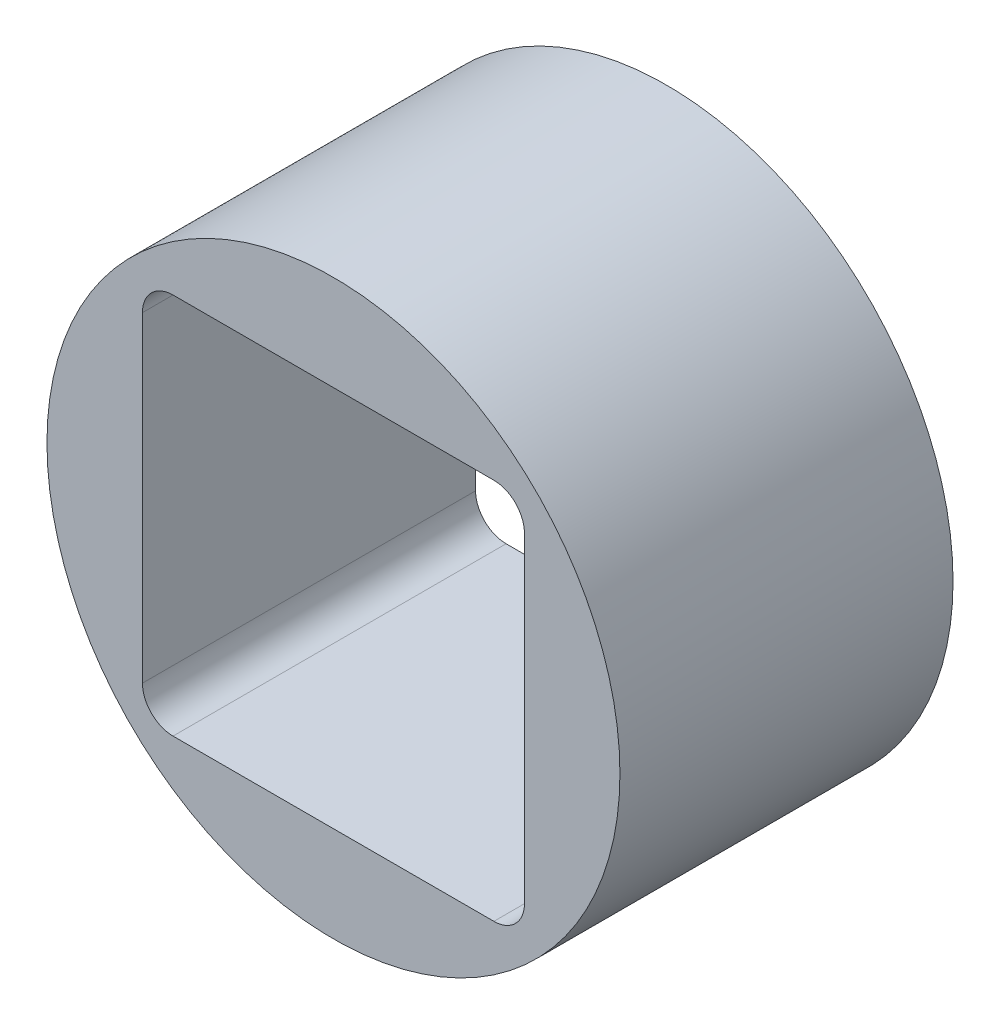
SolidWorks part; units mm, degrees
ref_plane "Front Plane" through (0, 0, 0) normal (0, 0, 1) x (1, 0, 0)
ref_plane "Top Plane" through (0, 0, 0) normal (0, 1, 0) x (1, 0, 0)
ref_plane "Right Plane" through (0, 0, 0) normal (1, 0, 0) x (0, 0, -1)
sketch "Sketch1" plane through (0, 0, 0) normal (0, 0, 1) x (1, 0, 0)
  line L5 (-2.667, 3.175) -> (2.667, 3.175)
  line L6 (-3.175, 2.667) -> (-3.175, -2.667)
  line L7 (-2.667, -3.175) -> (2.667, -3.175)
  line L8 (3.175, 2.667) -> (3.175, -2.667)
  line L9 (-3.175, 3.175) -> (3.175, -3.175) construction
  line L10 (-3.175, -3.175) -> (3.175, 3.175) construction
  circle A12 centre (0, 0) radius 4.7625
  arc A13 (-3.175, 2.667) -> (-2.667, 3.175) centre (-2.667, 2.667) cw
  arc A14 (2.667, -3.175) -> (3.175, -2.667) centre (2.667, -2.667) ccw
  arc A15 (2.667, 3.175) -> (3.175, 2.667) centre (2.667, 2.667) cw
  arc A16 (-2.667, -3.175) -> (-3.175, -2.667) centre (-2.667, -2.667) cw
  dimension "D1" = 9.525
  dimension "D4" = 0.508
  dimension "D2" = 6.35
  dimension "D3" = 6.35
extrude "Boss-Extrude1" add sketch "Sketch1" along normal blind 5.5372
